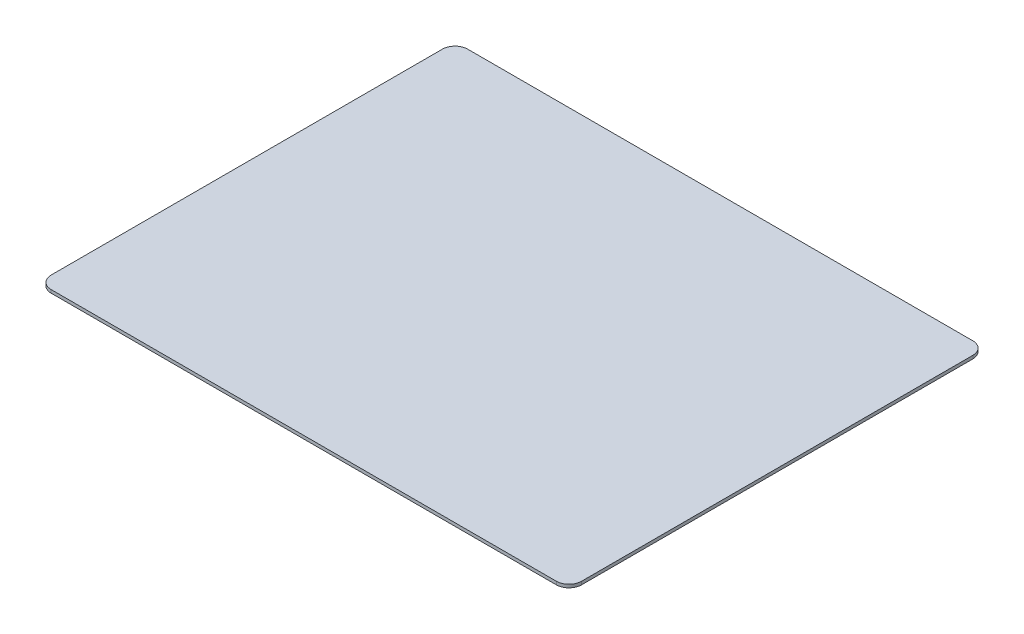
SolidWorks part; units mm, degrees
ref_plane "Front Plane" through (0, 0, 0) normal (0, 0, 1) x (1, 0, 0)
ref_plane "Top Plane" through (0, 0, 0) normal (0, 1, 0) x (1, 0, 0)
ref_plane "Right Plane" through (0, 0, 0) normal (1, 0, 0) x (0, 0, -1)
sketch "Sketch1" plane through (0, 0, 0) normal (0, 1, 0) x (1, 0, 0)
  line L1 (0, 0) -> (266.7, 0)
  line L2 (0, 0) -> (0, 209.423)
  line L3 (0, 209.423) -> (266.7, 209.423)
  line L4 (266.7, 0) -> (266.7, 209.423)
  dimension "D1" = 209.423
  dimension "D2" = 266.7
extrude "Boss-Extrude1" add sketch "Sketch1" along normal blind 1.5875
fillet "Fillet1" radius 6.35 4 edges at (0, 0.7937, 0) (0, 0.7937, -209.423) (266.7, 0.7937, -209.423) (266.7, 0.7937, 0)
